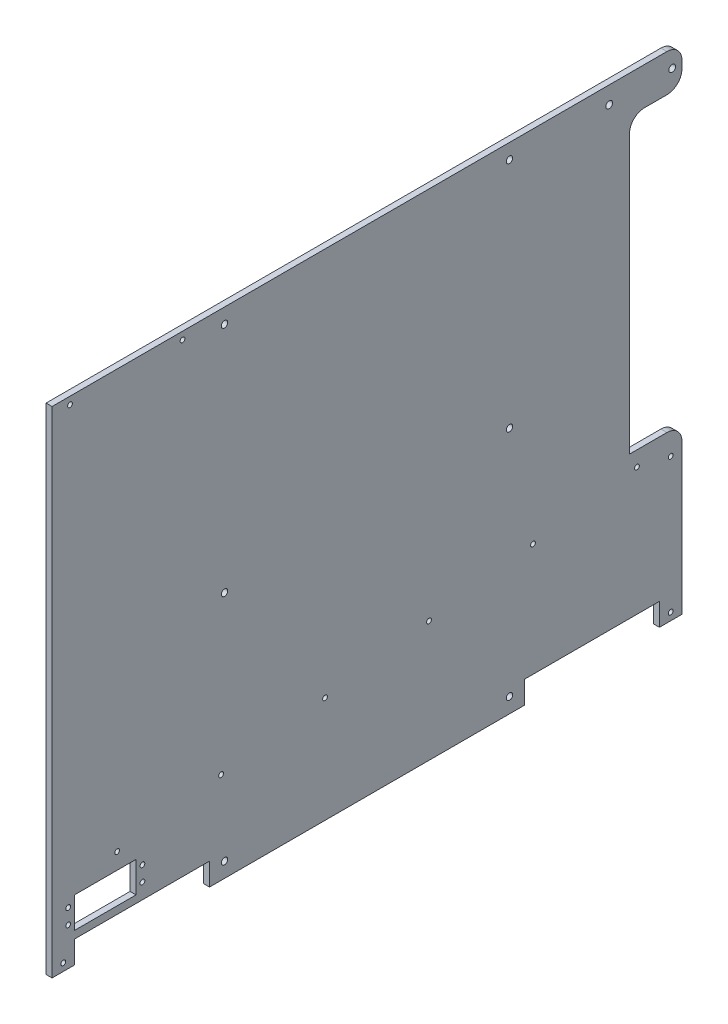
SolidWorks part; units mm, degrees
ref_plane "前视基准面" through (0, 0, 0) normal (0, 0, 1) x (1, 0, 0)
ref_plane "上视基准面" through (0, 0, 0) normal (0, 1, 0) x (1, 0, 0)
ref_plane "右视基准面" through (0, 0, 0) normal (1, 0, 0) x (0, 0, -1)
other "Configuration Table"
sketch "草图1" plane through (0, 0, 0) normal (1, 0, 0) x (0, 0, -1)
  line L1 (200, 165) -> (-210, 165)
  line L2 (210, 155) -> (210, -165)
  line L3 (210, -165) -> (-210, -165)
  line L4 (-210, 165) -> (-210, -165)
  line L5 (210, 165) -> (-210, -165) construction
  line L6 (210, -165) -> (-210, 165) construction
  arc A0 (200, 165) -> (210, 155) centre (200, 155) cw
  point P0 (0, 0)
  dimension "D3" = 10
  dimension "D1" = 420
  dimension "D2" = 330
extrude "凸台-拉伸1" add sketch "草图1" along normal blind 4
sketch "草图2" plane through (0, 0, 0) normal (1, 0, 0) x (0, 0, -1)
  line L0 (-210, -165) -> (210, -165) construction
  line L1 (-195, -165) -> (-105, -165)
  line L2 (-195, -165) -> (-195, -150)
  line L3 (-195, -150) -> (-105, -150)
  line L4 (-105, -165) -> (-105, -150)
  line L6 (-210, 165) -> (-210, -165) construction
  line L7 (-202.5, -165) -> (-202.5, -160) construction
  circle A0 centre (-202.5, -160) radius 1.6
  dimension "D5" = 3.2
  dimension "D1" = 105
  dimension "D2" = 15
  dimension "D3" = 15
  dimension "D6" = 5
  dimension "D7" = 7.5
extrude "切除-拉伸1" cut sketch "草图2" along normal through all
mirror "镜向1" about plane through (0, 0, 0) normal (0, 0, 1) of "切除-拉伸1"
sketch "草图3" plane through (4, 0, 0) normal (1, 0, 0) x (0, 0, -1)
  line L0 (210, -165) -> (210, 155) construction
  line L1 (-210, 165) -> (-210, -165) construction
  line L2 (200, 165) -> (-210, 165) construction
  line L3 (0, 0) -> (156.8733, 0) construction
  circle A0 centre (95, 155) radius 2.15
  circle A1 centre (-95, 155) radius 2.15
  circle A2 centre (95, -155) radius 2.15
  circle A3 centre (-95, -155) radius 2.15
  circle A4 centre (-95, 0) radius 2.15
  circle A5 centre (95, 0) radius 2.15
  dimension "D4" = 4.3
  dimension "D5" = 4.3
  dimension "D7" = 4.3
  dimension "D8" = 4.3
  dimension "D1" = 115
  dimension "D2" = 190
  dimension "D3" = 115
  dimension "D6" = 10
  dimension "D9" = 190
  dimension "D10" = 115
  dimension "D11" = 155
extrude "切除-拉伸3" cut sketch "草图3" against normal blind 5
sketch "草图4" plane through (4, 0, 0) normal (1, 0, 0) x (0, 0, -1)
  line L0 (210, -165) -> (210, 155) construction
  line L1 (200, 165) -> (-210, 165) construction
  line L2 (0, 262.5987) -> (0, -262.5987) construction
  circle A0 centre (203.5, 153.5) radius 2.25
  circle A1 centre (161.5, 153.5) radius 2.25
  point P12 (0, 0)
  dimension "D1" = 4.5
  dimension "D2" = 4.5
  dimension "D3" = 42
  dimension "D4" = 6.5
  dimension "D5" = 11.5
extrude "切除-拉伸5" cut sketch "草图4" against normal blind 5
sketch "草图5" plane through (4, 0, 0) normal (1, 0, 0) x (0, 0, -1)
  line L0 (210, -165) -> (210, 155) construction
  line L1 (210, 140) -> (175, 140)
  line L2 (210, 140) -> (210, -55)
  line L3 (210, -55) -> (175, -55)
  line L4 (175, 140) -> (175, -55)
  line L5 (200, 165) -> (-210, 165) construction
  line L6 (105, -150) -> (195, -150) construction
  dimension "D1" = 25
  dimension "D2" = 35
  dimension "D3" = 95
extrude "切除-拉伸6" cut sketch "草图5" against normal blind 5 contours L2 L1 L4 L3
sketch "草图8" plane through (0, 0, 0) normal (-1, 0, 0) x (0, 0, 1)
  line L0 (-210, -165) -> (-210, -55) construction
  line L1 (-195, -165) -> (-210, -165) construction
  line L2 (-180, -65) -> (-109.6834, -65) construction
  line L3 (-180, -65) -> (-108.5404, -75.043) construction
  circle A0 centre (-180, -65) radius 1.6
  circle A1 centre (-110.6812, -74.7421) radius 1.6
  circle A2 centre (-41.3625, -84.4842) radius 1.6
  circle A3 centre (27.9563, -94.2264) radius 1.6
  circle A4 centre (97.2751, -103.9685) radius 1.6
  circle A5 centre (166.5938, -113.7106) radius 1.6
  dimension "D1" = 30
  dimension "D3" = 3.2
  dimension "D2" = 100
  dimension "D4" = 8
  dimension "D6" = 70
  dimension "D5" = 6
extrude "切除-拉伸8" cut sketch "草图8" against normal blind 5
sketch "草图9" plane through (4, 0, 0) normal (1, 0, 0) x (0, 0, -1)
  line L0 (-210, 165) -> (-210, -165) construction
  line L1 (200, 165) -> (-210, 165) construction
  circle A0 centre (-198, 160) radius 1.6
  circle A1 centre (-123, 160) radius 1.6
  dimension "D1" = 75
  dimension "D4" = 3.2
  dimension "D5" = 3.2
  dimension "D2" = 12
  dimension "D3" = 5
extrude "切除-拉伸9" cut sketch "草图9" against normal blind 5
sketch "草图10" plane through (4, 0, 0) normal (1, 0, 0) x (0, 0, -1)
  line L0 (-105, -150) -> (-195, -150) construction
  line L1 (-195, -124.5) -> (-154, -124.5)
  line L2 (-195, -124.5) -> (-195, -145)
  line L3 (-195, -145) -> (-154, -145)
  line L4 (-154, -124.5) -> (-154, -145)
  line L5 (-210, 165) -> (-210, -165) construction
  line L6 (-174.5, -145) -> (-174.5, -121.4295) construction
  line L7 (-174.5, -121.4295) -> (-174.6186, -121.2814) construction
  circle A0 centre (-199.25, -129.75) radius 1.6
  circle A1 centre (-199.25, -139.75) radius 1.6
  circle A2 centre (-149.75, -139.75) radius 1.6
  circle A3 centre (-149.75, -129.75) radius 1.6
  dimension "D5" = 3.2
  dimension "D6" = 3.2
  dimension "D7" = 4.25
  dimension "D1" = 41
  dimension "D2" = 20.5
  dimension "D3" = 5
  dimension "D4" = 15
  dimension "D8" = 10
  dimension "D9" = 5.25
extrude "切除-拉伸10" cut sketch "草图10" against normal blind 5
fillet "圆角1" radius 10 3 edges at (2, 140, -210) (2, 140, -175) (2, -55, -210)
sketch "草图11" plane through (4, 0, 0) normal (1, 0, 0) x (0, 0, -1)
  line L0 (210, -165) -> (210, -65) construction
  circle A0 centre (202.5, -70) radius 1.6
  circle A1 centre (202.5, -160) radius 1.6 construction
  dimension "D1" = 3.2
  dimension "D2" = 90
  dimension "D3" = 7.5
extrude "切除-拉伸11" cut sketch "草图11" against normal blind 10
